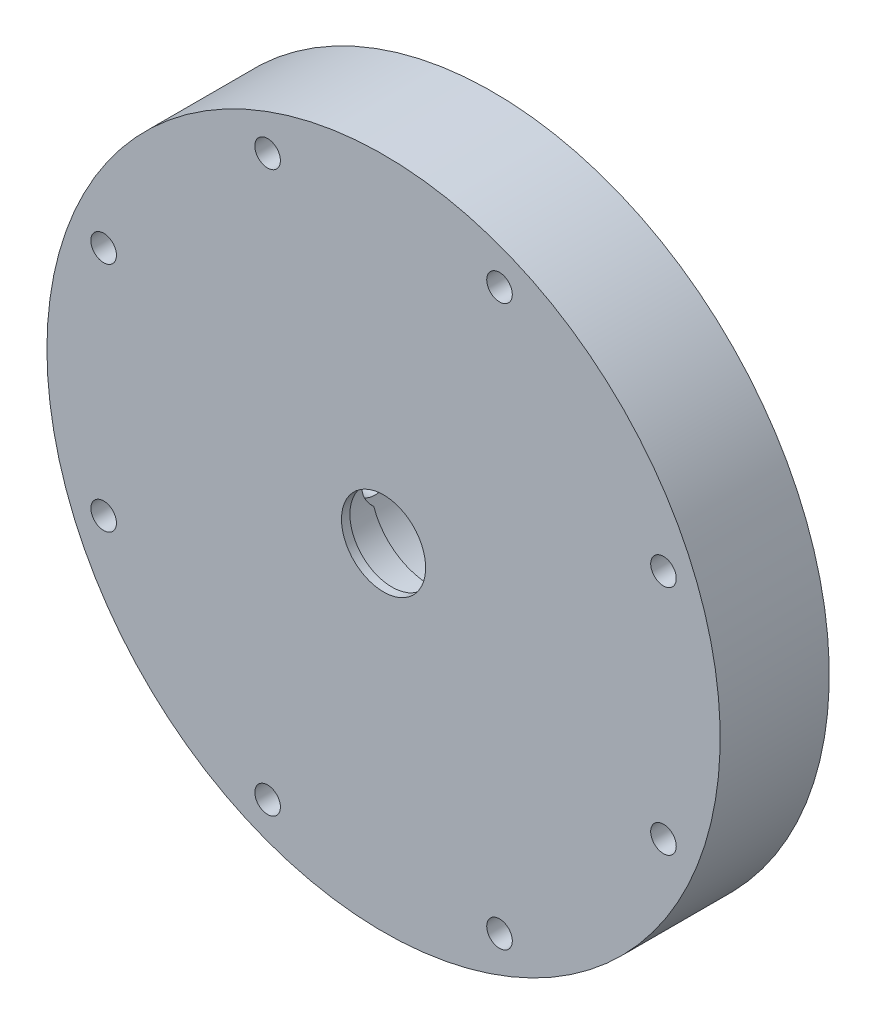
SolidWorks part; units mm, degrees
material "6061-T6 (SS)"
ref_plane "Front Plane" through (0, 0, 0) normal (0, 0, 1) x (1, 0, 0)
ref_plane "Top Plane" through (0, 0, 0) normal (0, 1, 0) x (1, 0, 0)
ref_plane "Right Plane" through (0, 0, 0) normal (1, 0, 0) x (0, 0, -1)
sketch "Sketch16" plane through (0, 0, 0) normal (0, 1, 0) x (1, 0, 0)
  line L0 (7.9375, -25.4) -> (63.5, -25.4)
  line L1 (63.5, -25.4) -> (63.5, 0)
  line L2 (63.5, 0) -> (14.2875, 0)
  line L3 (14.2875, 0) -> (14.2875, -16.6688)
  line L4 (14.2875, -16.6688) -> (11.176, -16.6688)
  line L5 (11.176, -16.6688) -> (11.176, -23.8125)
  line L6 (11.176, -23.8125) -> (7.9375, -23.8125)
  line L7 (7.9375, -23.8125) -> (7.9375, -25.4)
  line L8 (0, 0) -> (0, -25.4) construction
  dimension "D1" = 127
  dimension "D2" = 15.875
  dimension "D3" = 25.4
  dimension "D4" = 1.5875
  dimension "D5" = 7.1437
  dimension "D6" = 22.352
  dimension "D7" = 28.575
revolve "Revolve1" add sketch "Sketch16" angle 360 about L8
sketch "Sketch4" plane through (0, 0, 25.4) normal (0, 0, 1) x (1, 0, 0)
  line L0 (52.7997, -21.8704) -> (58.6664, -24.3004) construction
  line L1 (0, 0) -> (63.5, 0) construction
  circle A0 centre (52.7997, -21.8704) radius 2.413
  circle A2 centre (0, 0) radius 63.5 construction
  dimension "D1" = 4.826
  dimension "D2" = 6.35
  dimension "D3" = 22.5
extrude "Cut-Extrude1" cut sketch "Sketch4" against normal through all
pattern_circular "CirPattern1" count 8 over 360 about axis through (0, 0, 0) along (0, 0, 1) of "Cut-Extrude1"
curve "Curve1"
  spline degree 3 poles (34.3588, 0, 0) (34.3618, -0.072, 0) (34.3677, -0.2162, 0) (34.3749, -0.4324, 0) (34.3809, -0.6488, 0) (34.3855, -0.8653, 0) (34.3887, -1.0818, 0) (34.3906, -1.2984, 0) (34.3911, -1.5151, 0) (34.3903, -1.7318, 0) (34.3881, -1.9486, 0) (34.3846, -2.1655, 0) (34.3797, -2.3823, 0) (34.3735, -2.5992, 0) (34.3659, -2.8162, 0) (34.3569, -3.0331, 0) (34.3466, -3.25, 0) (34.3349, -3.4669, 0) (34.3218, -3.6838, 0) (34.3074, -3.9006, 0) (34.2916, -4.1175, 0) (34.2745, -4.3343, 0) (34.256, -4.551, 0) (34.2361, -4.7677, 0) (34.2149, -4.9843, 0) (34.1923, -5.2008, 0) (34.1683, -5.4172, 0) (34.143, -5.6336, 0) (34.1163, -5.8498, 0) (34.0882, -6.066, 0) (34.0588, -6.282, 0) (34.028, -6.4979, 0) (33.9959, -6.7136, 0) (33.9624, -6.9292, 0) (33.9275, -7.1446, 0) (33.8913, -7.3599, 0) (33.8537, -7.575, 0) (33.8147, -7.79, 0) (33.7744, -8.0047, 0) (33.7327, -8.2192, 0) (33.6897, -8.4336, 0) (33.6453, -8.6477, 0) (33.5996, -8.8616, 0) (33.5525, -9.0752, 0) (33.504, -9.2887, 0) (33.4542, -9.5018, 0) (33.4031, -9.7147, 0) (33.3506, -9.9274, 0) (33.2967, -10.1398, 0) (33.2415, -10.3519, 0) (33.1849, -10.5637, 0) (33.127, -10.7752, 0) (33.0678, -10.9863, 0) (33.0072, -11.1972, 0) (32.9453, -11.4078, 0) (32.882, -11.618, 0) (32.8174, -11.8278, 0) (32.7515, -12.0373, 0) (32.6842, -12.2465, 0) (32.6156, -12.4553, 0) (32.5457, -12.6637, 0) (32.4744, -12.8717, 0) (32.4018, -13.0793, 0) (32.3279, -13.2866, 0) (32.2527, -13.4934, 0) (32.1761, -13.6998, 0) (32.0982, -13.9057, 0) (32.0191, -14.1113, 0) (31.9386, -14.3164, 0) (31.8568, -14.521, 0) (31.7736, -14.7252, 0) (31.6892, -14.9289, 0) (31.6035, -15.1321, 0) (31.5165, -15.3348, 0) (31.4282, -15.5371, 0) (31.3386, -15.7388, 0) (31.2477, -15.9401, 0) (31.1555, -16.1408, 0) (31.062, -16.341, 0) (30.9672, -16.5406, 0) (30.8712, -16.7397, 0) (30.7739, -16.9383, 0) (30.6753, -17.1362, 0) (30.5754, -17.3337, 0) (30.4743, -17.5305, 0) (30.3719, -17.7268, 0) (30.2682, -17.9224, 0) (30.1633, -18.1175, 0) (30.0572, -18.312, 0) (29.9497, -18.5058, 0) (29.8411, -18.699, 0) (29.7312, -18.8916, 0) (29.62, -19.0835, 0) (29.5077, -19.2748, 0) (29.394, -19.4655, 0) (29.2792, -19.6554, 0) (29.1631, -19.8447, 0) (29.0459, -20.0334, 0) (28.9273, -20.2213, 0) (28.8076, -20.4085, 0) (28.6867, -20.595, 0) (28.5646, -20.7809, 0) (28.4413, -20.966, 0) (28.3167, -21.1503, 0) (28.191, -21.334, 0) (28.0641, -21.5168, 0) (27.936, -21.699, 0) (27.8068, -21.8804, 0) (27.6763, -22.061, 0) (27.5447, -22.2408, 0) (27.4119, -22.4199, 0) (27.278, -22.5981, 0) (27.1429, -22.7756, 0) (27.0067, -22.9523, 0) (26.8693, -23.1281, 0) (26.7307, -23.3032, 0) (26.5911, -23.4774, 0) (26.4503, -23.6508, 0) (26.3083, -23.8233, 0) (26.1653, -23.995, 0) (26.0211, -24.1659, 0) (25.8758, -24.3358, 0) (25.7295, -24.5049, 0) (25.582, -24.6732, 0) (25.4334, -24.8405, 0) (25.2837, -25.007, 0) (25.1329, -25.1725, 0) (24.9811, -25.3372, 0) (24.8282, -25.5009, 0) (24.6742, -25.6637, 0) (24.5191, -25.8256, 0) (24.363, -25.9866, 0) (24.2059, -26.1466, 0) (24.0477, -26.3056, 0) (23.8884, -26.4638, 0) (23.7281, -26.6209, 0) (23.5668, -26.7771, 0) (23.4045, -26.9323, 0) (23.2411, -27.0866, 0) (23.0767, -27.2398, 0) (22.9113, -27.392, 0) (22.745, -27.5433, 0) (22.5776, -27.6935, 0) (22.4092, -27.8428, 0) (22.2399, -27.991, 0) (22.0695, -28.1382, 0) (21.8983, -28.2843, 0) (21.726, -28.4294, 0) (21.5528, -28.5735, 0) (21.3786, -28.7165, 0) (21.2035, -28.8584, 0) (21.0274, -28.9993, 0) (20.8505, -29.1391, 0) (20.6726, -29.2779, 0) (20.4937, -29.4155, 0) (20.314, -29.5521, 0) (20.1333, -29.6875, 0) (19.9518, -29.8219, 0) (19.7694, -29.9552, 0) (19.586, -30.0873, 0) (19.4018, -30.2183, 0) (19.2167, -30.3482, 0) (19.0308, -30.477, 0) (18.844, -30.6046, 0) (18.6564, -30.7311, 0) (18.4679, -30.8565, 0) (18.2785, -30.9807, 0) (18.0884, -31.1037, 0) (17.8974, -31.2256, 0) (17.7056, -31.3462, 0) (17.513, -31.4658, 0) (17.3195, -31.5841, 0) (17.1253, -31.7013, 0) (16.9303, -31.8172, 0) (16.7346, -31.932, 0) (16.538, -32.0455, 0) (16.3407, -32.1579, 0) (16.1426, -32.269, 0) (15.9438, -32.379, 0) (15.7442, -32.4877, 0) (15.5439, -32.5951, 0) (15.3429, -32.7014, 0) (15.1411, -32.8064, 0) (14.9387, -32.9101, 0) (14.7355, -33.0127, 0) (14.5316, -33.1139, 0) (14.3271, -33.2139, 0) (14.1218, -33.3127, 0) (13.9159, -33.4102, 0) (13.7093, -33.5064, 0) (13.5021, -33.6013, 0) (13.2942, -33.6949, 0) (13.0857, -33.7873, 0) (12.8765, -33.8784, 0) (12.6667, -33.9682, 0) (12.4563, -34.0567, 0) (12.2453, -34.1439, 0) (12.0336, -34.2297, 0) (11.8214, -34.3143, 0) (11.6086, -34.3976, 0) (11.3952, -34.4795, 0) (11.1812, -34.5601, 0) (10.9667, -34.6394, 0) (10.7516, -34.7174, 0) (10.536, -34.794, 0) (10.3198, -34.8693, 0) (10.1031, -34.9433, 0) (9.8859, -35.0159, 0) (9.6682, -35.0871, 0) (9.4499, -35.1571, 0) (9.2312, -35.2256, 0) (9.012, -35.2928, 0) (8.7923, -35.3586, 0) (8.5721, -35.4231, 0) (8.3515, -35.4862, 0) (8.1304, -35.5479, 0) (7.9088, -35.6083, 0) (7.6869, -35.6672, 0) (7.4645, -35.7248, 0) (7.2416, -35.781, 0) (7.0184, -35.8359, 0) (6.7948, -35.8893, 0) (6.5708, -35.9413, 0) (6.3463, -35.992, 0) (6.1216, -36.0412, 0) (5.8964, -36.089, 0) (5.6709, -36.1355, 0) (5.445, -36.1805, 0) (5.2188, -36.2241, 0) (4.9923, -36.2663, 0) (4.7654, -36.3071, 0) (4.5382, -36.3464, 0) (4.3107, -36.3844, 0) (4.0829, -36.4209, 0) (3.8549, -36.456, 0) (3.6265, -36.4897, 0) (3.3979, -36.5219, 0) (3.169, -36.5527, 0) (2.9398, -36.5821, 0) (2.7105, -36.6101, 0) (2.4808, -36.6366, 0) (2.251, -36.6617, 0) (2.0209, -36.6853, 0) (1.7907, -36.7075, 0) (1.5602, -36.7282, 0) (1.3295, -36.7475, 0) (1.0987, -36.7654, 0) (0.8677, -36.7818, 0) (0.6365, -36.7967, 0) (0.4052, -36.8103, 0) (0.1737, -36.8223, 0) (-0.0579, -36.8329, 0) (-0.2897, -36.842, 0) (-0.5215, -36.8497, 0) (-0.7535, -36.856, 0) (-0.9855, -36.8607, 0) (-1.2177, -36.8641, 0) (-1.4499, -36.8659, 0) (-1.6822, -36.8663, 0) (-1.9146, -36.8652, 0) (-2.147, -36.8627, 0) (-2.3795, -36.8587, 0) (-2.612, -36.8532, 0) (-2.8445, -36.8463, 0) (-3.077, -36.8379, 0) (-3.3096, -36.828, 0) (-3.5421, -36.8167, 0) (-3.7747, -36.8039, 0) (-4.0072, -36.7897, 0) (-4.2397, -36.7739, 0) (-4.4721, -36.7567, 0) (-4.7045, -36.7381, 0) (-4.9368, -36.718, 0) (-5.1691, -36.6964, 0) (-5.4013, -36.6733, 0) (-5.6334, -36.6488, 0) (-5.8654, -36.6228, 0) (-6.0973, -36.5953, 0) (-6.3291, -36.5664, 0) (-6.5608, -36.536, 0) (-6.7924, -36.5041, 0) (-7.0238, -36.4708, 0) (-7.255, -36.436, 0) (-7.4861, -36.3997, 0) (-7.717, -36.362, 0) (-7.9478, -36.3228, 0) (-8.1783, -36.2821, 0) (-8.4087, -36.24, 0) (-8.6389, -36.1964, 0) (-8.8688, -36.1514, 0) (-9.0985, -36.1049, 0) (-9.328, -36.057, 0) (-9.5572, -36.0076, 0) (-9.7862, -35.9567, 0) (-10.015, -35.9044, 0) (-10.2434, -35.8506, 0) (-10.4716, -35.7954, 0) (-10.6995, -35.7387, 0) (-10.9271, -35.6806, 0) (-11.1543, -35.621, 0) (-11.3813, -35.56, 0) (-11.608, -35.4975, 0) (-11.8343, -35.4336, 0) (-12.0602, -35.3683, 0) (-12.2858, -35.3015, 0) (-12.5111, -35.2333, 0) (-12.7359, -35.1636, 0) (-12.9604, -35.0925, 0) (-13.1845, -35.02, 0) (-13.4082, -34.946, 0) (-13.6315, -34.8707, 0) (-13.8544, -34.7939, 0) (-14.0769, -34.7156, 0) (-14.2989, -34.636, 0) (-14.5204, -34.5549, 0) (-14.7416, -34.4724, 0) (-14.9622, -34.3885, 0) (-15.1824, -34.3032, 0) (-15.4021, -34.2165, 0) (-15.6213, -34.1284, 0) (-15.84, -34.0389, 0) (-16.0582, -33.948, 0) (-16.2759, -33.8556, 0) (-16.4931, -33.7619, 0) (-16.7097, -33.6668, 0) (-16.9258, -33.5703, 0) (-17.1414, -33.4725, 0) (-17.3563, -33.3732, 0) (-17.5707, -33.2726, 0) (-17.7846, -33.1705, 0) (-17.9978, -33.0672, 0) (-18.2104, -32.9624, 0) (-18.4225, -32.8563, 0) (-18.6339, -32.7488, 0) (-18.8447, -32.64, 0) (-19.0549, -32.5298, 0) (-19.2644, -32.4182, 0) (-19.4733, -32.3053, 0) (-19.6815, -32.1911, 0) (-19.8891, -32.0755, 0) (-20.0959, -31.9586, 0) (-20.3022, -31.8403, 0) (-20.5077, -31.7208, 0) (-20.7125, -31.5999, 0) (-20.9166, -31.4776, 0) (-21.1199, -31.3541, 0) (-21.3226, -31.2293, 0) (-21.5245, -31.1031, 0) (-21.7257, -30.9756, 0) (-21.9261, -30.8469, 0) (-22.1258, -30.7168, 0) (-22.3247, -30.5855, 0) (-22.5228, -30.4529, 0) (-22.7202, -30.319, 0) (-22.9167, -30.1838, 0) (-23.1125, -30.0473, 0) (-23.3074, -29.9096, 0) (-23.5015, -29.7706, 0) (-23.6948, -29.6303, 0) (-23.8873, -29.4888, 0) (-24.0789, -29.3461, 0) (-24.2697, -29.2021, 0) (-24.4596, -29.0569, 0) (-24.6486, -28.9104, 0) (-24.8368, -28.7627, 0) (-25.0241, -28.6138, 0) (-25.2105, -28.4637, 0) (-25.396, -28.3124, 0) (-25.5806, -28.1598, 0) (-25.7643, -28.0061, 0) (-25.9471, -27.8511, 0) (-26.1289, -27.695, 0) (-26.3098, -27.5377, 0) (-26.4897, -27.3792, 0) (-26.6687, -27.2195, 0) (-26.8468, -27.0587, 0) (-27.0239, -26.8967, 0) (-27.2, -26.7335, 0) (-27.3751, -26.5692, 0) (-27.5492, -26.4038, 0) (-27.7223, -26.2372, 0) (-27.8945, -26.0695, 0) (-28.0656, -25.9006, 0) (-28.2357, -25.7306, 0) (-28.4047, -25.5596, 0) (-28.5728, -25.3874, 0) (-28.7398, -25.2141, 0) (-28.9057, -25.0397, 0) (-29.0706, -24.8642, 0) (-29.2344, -24.6877, 0) (-29.3972, -24.51, 0) (-29.5588, -24.3313, 0) (-29.7194, -24.1515, 0) (-29.8789, -23.9707, 0) (-30.0374, -23.7888, 0) (-30.1947, -23.6059, 0) (-30.3508, -23.422, 0) (-30.5059, -23.237, 0) (-30.6599, -23.051, 0) (-30.8127, -22.864, 0) (-30.9643, -22.6759, 0) (-31.1149, -22.4869, 0) (-31.2642, -22.2968, 0) (-31.4125, -22.1058, 0) (-31.5595, -21.9138, 0) (-31.7054, -21.7208, 0) (-31.8501, -21.5269, 0) (-31.9936, -21.332, 0) (-32.1359, -21.1361, 0) (-32.2771, -20.9393, 0) (-32.417, -20.7416, 0) (-32.5557, -20.5429, 0) (-32.6932, -20.3433, 0) (-32.8295, -20.1428, 0) (-32.9646, -19.9414, 0) (-33.0984, -19.739, 0) (-33.231, -19.5358, 0) (-33.3623, -19.3317, 0) (-33.4924, -19.1267, 0) (-33.6212, -18.9209, 0) (-33.7488, -18.7142, 0) (-33.875, -18.5066, 0) (-34.0001, -18.2982, 0) (-34.1238, -18.0889, 0) (-34.2462, -17.8788, 0) (-34.3674, -17.6679, 0) (-34.4873, -17.4562, 0) (-34.6058, -17.2436, 0) (-34.7231, -17.0303, 0) (-34.839, -16.8161, 0) (-34.9536, -16.6012, 0) (-35.0669, -16.3855, 0) (-35.1789, -16.1691, 0) (-35.2895, -15.9518, 0) (-35.3988, -15.7339, 0) (-35.5067, -15.5152, 0) (-35.6133, -15.2957, 0) (-35.7186, -15.0755, 0) (-35.8224, -14.8546, 0) (-35.925, -14.633, 0) (-36.0261, -14.4107, 0) (-36.1259, -14.1877, 0) (-36.2243, -13.964, 0) (-36.3213, -13.7397, 0) (-36.4169, -13.5146, 0) (-36.5111, -13.289, 0) (-36.604, -13.0626, 0) (-36.6954, -12.8356, 0) (-36.7854, -12.608, 0) (-36.874, -12.3798, 0) (-36.9612, -12.1509, 0) (-37.047, -11.9215, 0) (-37.1314, -11.6914, 0) (-37.2143, -11.4608, 0) (-37.2958, -11.2295, 0) (-37.3758, -10.9977, 0) (-37.4545, -10.7654, 0) (-37.5316, -10.5325, 0) (-37.6074, -10.299, 0) (-37.6817, -10.065, 0) (-37.7545, -9.8305, 0) (-37.8259, -9.5955, 0) (-37.8958, -9.3599, 0) (-37.9642, -9.1239, 0) (-38.0312, -8.8873, 0) (-38.0967, -8.6503, 0) (-38.1607, -8.4128, 0) (-38.2232, -8.1749, 0) (-38.2843, -7.9364, 0) (-38.3439, -7.6976, 0) (-38.402, -7.4583, 0) (-38.4586, -7.2186, 0) (-38.5137, -6.9785, 0) (-38.5673, -6.7379, 0) (-38.6194, -6.497, 0) (-38.67, -6.2557, 0) (-38.7191, -6.014, 0) (-38.7666, -5.7719, 0) (-38.8127, -5.5295, 0) (-38.8573, -5.2867, 0) (-38.9003, -5.0435, 0) (-38.9418, -4.8001, 0) (-38.9818, -4.5563, 0) (-39.0203, -4.3122, 0) (-39.0572, -4.0678, 0) (-39.0926, -3.8231, 0) (-39.1265, -3.5781, 0) (-39.1589, -3.3329, 0) (-39.1897, -3.0874, 0) (-39.2189, -2.8416, 0) (-39.2467, -2.5956, 0) (-39.2729, -2.3493, 0) (-39.2975, -2.1029, 0) (-39.3206, -1.8562, 0) (-39.3422, -1.6093, 0) (-39.3622, -1.3622, 0) (-39.3806, -1.1149, 0) (-39.3975, -0.8674, 0) (-39.4129, -0.6198, 0) (-39.4266, -0.372, 0) (-39.4389, -0.124, 0) (-39.4496, 0.1241, 0) (-39.4587, 0.3723, 0) (-39.4662, 0.6206, 0) (-39.4722, 0.8691, 0) (-39.4766, 1.1176, 0) (-39.4795, 1.3662, 0) (-39.4808, 1.6149, 0) (-39.4806, 1.8637, 0) (-39.4787, 2.1126, 0) (-39.4753, 2.3615, 0) (-39.4704, 2.6104, 0) (-39.4638, 2.8594, 0) (-39.4557, 3.1084, 0) (-39.446, 3.3574, 0) (-39.4348, 3.6064, 0) (-39.422, 3.8554, 0) (-39.4076, 4.1043, 0) (-39.3916, 4.3533, 0) (-39.3741, 4.6022, 0) (-39.355, 4.851, 0) (-39.3343, 5.0998, 0) (-39.3121, 5.3486, 0) (-39.2883, 5.5972, 0) (-39.2629, 5.8458, 0) (-39.2359, 6.0943, 0) (-39.2074, 6.3426, 0) (-39.1773, 6.5909, 0) (-39.1456, 6.839, 0) (-39.1124, 7.087, 0) (-39.0776, 7.3348, 0) (-39.0412, 7.5825, 0) (-39.0033, 7.83, 0) (-38.9637, 8.0773, 0) (-38.9227, 8.3245, 0) (-38.88, 8.5714, 0) (-38.8358, 8.8181, 0) (-38.79, 9.0647, 0) (-38.7427, 9.311, 0) (-38.6938, 9.557, 0) (-38.6433, 9.8028, 0) (-38.5913, 10.0484, 0) (-38.5377, 10.2937, 0) (-38.4825, 10.5387, 0) (-38.4258, 10.7834, 0) (-38.3676, 11.0279, 0) (-38.3077, 11.272, 0) (-38.2464, 11.5158, 0) (-38.1835, 11.7593, 0) (-38.119, 12.0024, 0) (-38.053, 12.2452, 0) (-37.9854, 12.4877, 0) (-37.9163, 12.7297, 0) (-37.8457, 12.9715, 0) (-37.7735, 13.2128, 0) (-37.6998, 13.4537, 0) (-37.6246, 13.6942, 0) (-37.5478, 13.9343, 0) (-37.4694, 14.174, 0) (-37.3896, 14.4133, 0) (-37.3082, 14.6521, 0) (-37.2253, 14.8904, 0) (-37.1409, 15.1283, 0) (-37.055, 15.3658, 0) (-36.9675, 15.6027, 0) (-36.8786, 15.8391, 0) (-36.7881, 16.0751, 0) (-36.6961, 16.3105, 0) (-36.6026, 16.5454, 0) (-36.5076, 16.7798, 0) (-36.4111, 17.0137, 0) (-36.3131, 17.247, 0) (-36.2136, 17.4797, 0) (-36.1127, 17.7119, 0) (-36.0102, 17.9434, 0) (-35.9063, 18.1744, 0) (-35.8008, 18.4048, 0) (-35.6939, 18.6346, 0) (-35.5856, 18.8638, 0) (-35.4757, 19.0924, 0) (-35.3644, 19.3203, 0) (-35.2516, 19.5476, 0) (-35.1374, 19.7742, 0) (-35.0217, 20.0001, 0) (-34.9046, 20.2254, 0) (-34.786, 20.45, 0) (-34.666, 20.6739, 0) (-34.5445, 20.8972, 0) (-34.4216, 21.1197, 0) (-34.2973, 21.3414, 0) (-34.1715, 21.5625, 0) (-34.0443, 21.7828, 0) (-33.9157, 22.0024, 0) (-33.7857, 22.2212, 0) (-33.6542, 22.4393, 0) (-33.5214, 22.6565, 0) (-33.3872, 22.873, 0) (-33.2515, 23.0887, 0) (-33.1145, 23.3036, 0) (-32.9761, 23.5177, 0) (-32.8363, 23.731, 0) (-32.6951, 23.9434, 0) (-32.5526, 24.1551, 0) (-32.4087, 24.3658, 0) (-32.2634, 24.5757, 0) (-32.1168, 24.7848, 0) (-31.9688, 24.993, 0) (-31.8194, 25.2003, 0) (-31.6688, 25.4067, 0) (-31.5168, 25.6122, 0) (-31.3634, 25.8168, 0) (-31.2087, 26.0205, 0) (-31.0528, 26.2232, 0) (-30.8954, 26.425, 0) (-30.7368, 26.6259, 0) (-30.5769, 26.8259, 0) (-30.4157, 27.0249, 0) (-30.2532, 27.2229, 0) (-30.0894, 27.4199, 0) (-29.9243, 27.616, 0) (-29.758, 27.8111, 0) (-29.5903, 28.0051, 0) (-29.4214, 28.1982, 0) (-29.2513, 28.3902, 0) (-29.0799, 28.5812, 0) (-28.9073, 28.7712, 0) (-28.7334, 28.9602, 0) (-28.5583, 29.1481, 0) (-28.3819, 29.3349, 0) (-28.2044, 29.5207, 0) (-28.0256, 29.7054, 0) (-27.8456, 29.889, 0) (-27.6644, 30.0716, 0) (-27.4821, 30.253, 0) (-27.2985, 30.4334, 0) (-27.1138, 30.6126, 0) (-26.9279, 30.7907, 0) (-26.7408, 30.9677, 0) (-26.5525, 31.1435, 0) (-26.3631, 31.3182, 0) (-26.1726, 31.4918, 0) (-25.9809, 31.6642, 0) (-25.7881, 31.8354, 0) (-25.5941, 32.0055, 0) (-25.3991, 32.1744, 0) (-25.2029, 32.3421, 0) (-25.0056, 32.5086, 0) (-24.8073, 32.6739, 0) (-24.6078, 32.8379, 0) (-24.4073, 33.0008, 0) (-24.2056, 33.1625, 0) (-24.003, 33.3229, 0) (-23.7992, 33.4821, 0) (-23.5944, 33.64, 0) (-23.3886, 33.7967, 0) (-23.1817, 33.9521, 0) (-22.9738, 34.1063, 0) (-22.7649, 34.2592, 0) (-22.5549, 34.4108, 0) (-22.344, 34.5612, 0) (-22.132, 34.7102, 0) (-21.9191, 34.8579, 0) (-21.7051, 35.0044, 0) (-21.4902, 35.1495, 0) (-21.2744, 35.2933, 0) (-21.0576, 35.4358, 0) (-20.8398, 35.577, 0) (-20.6211, 35.7168, 0) (-20.4014, 35.8552, 0) (-20.1809, 35.9924, 0) (-19.9594, 36.1281, 0) (-19.737, 36.2626, 0) (-19.5137, 36.3956, 0) (-19.2895, 36.5273, 0) (-19.0644, 36.6576, 0) (-18.8384, 36.7865, 0) (-18.6116, 36.914, 0) (-18.3839, 37.0401, 0) (-18.1554, 37.1648, 0) (-17.926, 37.2881, 0) (-17.6958, 37.41, 0) (-17.4648, 37.5305, 0) (-17.233, 37.6495, 0) (-17.0003, 37.7671, 0) (-16.7669, 37.8833, 0) (-16.5327, 37.998, 0) (-16.2976, 38.1113, 0) (-16.0619, 38.2231, 0) (-15.8253, 38.3335, 0) (-15.588, 38.4424, 0) (-15.35, 38.5499, 0) (-15.1112, 38.6559, 0) (-14.8717, 38.7604, 0) (-14.6315, 38.8634, 0) (-14.3906, 38.9649, 0) (-14.1489, 39.0649, 0) (-13.9066, 39.1635, 0) (-13.6636, 39.2605, 0) (-13.42, 39.356, 0) (-13.1757, 39.4501, 0) (-12.9307, 39.5426, 0) (-12.6851, 39.6335, 0) (-12.4388, 39.723, 0) (-12.1919, 39.8109, 0) (-11.9445, 39.8973, 0) (-11.6964, 39.9822, 0) (-11.4477, 40.0655, 0) (-11.1984, 40.1473, 0) (-10.9486, 40.2275, 0) (-10.6982, 40.3062, 0) (-10.4472, 40.3833, 0) (-10.1957, 40.4588, 0) (-9.9436, 40.5328, 0) (-9.6911, 40.6052, 0) (-9.438, 40.676, 0) (-9.1844, 40.7453, 0) (-8.9303, 40.813, 0) (-8.6757, 40.8791, 0) (-8.4206, 40.9436, 0) (-8.1651, 41.0065, 0) (-7.9091, 41.0679, 0) (-7.6526, 41.1276, 0) (-7.3958, 41.1857, 0) (-7.1385, 41.2422, 0) (-6.8807, 41.2972, 0) (-6.6226, 41.3505, 0) (-6.3641, 41.4022, 0) (-6.1051, 41.4523, 0) (-5.8458, 41.5007, 0) (-5.5862, 41.5476, 0) (-5.3262, 41.5928, 0) (-5.0658, 41.6364, 0) (-4.8051, 41.6784, 0) (-4.544, 41.7187, 0) (-4.2827, 41.7574, 0) (-4.021, 41.7944, 0) (-3.7591, 41.8299, 0) (-3.4968, 41.8637, 0) (-3.2343, 41.8958, 0) (-2.9715, 41.9263, 0) (-2.7085, 41.9551, 0) (-2.4452, 41.9823, 0) (-2.1817, 42.0079, 0) (-1.9179, 42.0318, 0) (-1.654, 42.054, 0) (-1.3898, 42.0746, 0) (-1.1254, 42.0935, 0) (-0.8609, 42.1108, 0) (-0.5962, 42.1264, 0) (-0.3313, 42.1403, 0) (-0.0663, 42.1526, 0) (0.1989, 42.1632, 0) (0.4642, 42.1721, 0) (0.7296, 42.1794, 0) (0.9952, 42.185, 0) (1.2608, 42.1889, 0) (1.5265, 42.1912, 0) (1.7923, 42.1918, 0) (2.0582, 42.1907, 0) (2.3241, 42.1879, 0) (2.5901, 42.1835, 0) (2.8561, 42.1774, 0) (3.1221, 42.1696, 0) (3.3881, 42.1601, 0) (3.6542, 42.149, 0) (3.9202, 42.1362, 0) (4.1863, 42.1217, 0) (4.4523, 42.1055, 0) (4.7182, 42.0876, 0) (4.9841, 42.0681, 0) (5.25, 42.0469, 0) (5.5158, 42.024, 0) (5.7815, 41.9994, 0) (6.0471, 41.9732, 0) (6.3126, 41.9452, 0) (6.578, 41.9156, 0) (6.8433, 41.8843, 0) (7.1084, 41.8514, 0) (7.3734, 41.8167, 0) (7.6383, 41.7804, 0) (7.903, 41.7424, 0) (8.1675, 41.7027, 0) (8.4318, 41.6614, 0) (8.6959, 41.6184, 0) (8.9598, 41.5737, 0) (9.2235, 41.5273, 0) (9.487, 41.4792, 0) (9.7502, 41.4295, 0) (10.0132, 41.3782, 0) (10.2759, 41.3251, 0) (10.5384, 41.2704, 0) (10.8005, 41.214, 0) (11.0624, 41.156, 0) (11.324, 41.0962, 0) (11.5852, 41.0349, 0) (11.8462, 40.9718, 0) (12.1068, 40.9071, 0) (12.367, 40.8408, 0) (12.6269, 40.7728, 0) (12.8865, 40.7031, 0) (13.1456, 40.6318, 0) (13.4044, 40.5589, 0) (13.6628, 40.4843, 0) (13.9207, 40.408, 0) (14.1783, 40.3302, 0) (14.4354, 40.2506, 0) (14.6921, 40.1695, 0) (14.9483, 40.0867, 0) (15.2041, 40.0022, 0) (15.4594, 39.9161, 0) (15.7142, 39.8285, 0) (15.9685, 39.7391, 0) (16.2223, 39.6482, 0) (16.4756, 39.5556, 0) (16.7284, 39.4614, 0) (16.9807, 39.3656, 0) (17.2324, 39.2682, 0) (17.4836, 39.1692, 0) (17.7342, 39.0686, 0) (17.9842, 38.9664, 0) (18.2336, 38.8626, 0) (18.4825, 38.7571, 0) (18.7307, 38.6501, 0) (18.9783, 38.5415, 0) (19.2254, 38.4313, 0) (19.4717, 38.3196, 0) (19.7174, 38.2062, 0) (19.9625, 38.0913, 0) (20.2069, 37.9748, 0) (20.4506, 37.8568, 0) (20.6937, 37.7372, 0) (20.936, 37.616, 0) (21.1777, 37.4933, 0) (21.4186, 37.369, 0) (21.6588, 37.2431, 0) (21.8983, 37.1158, 0) (22.137, 36.9869, 0) (22.3749, 36.8564, 0) (22.6121, 36.7244, 0) (22.8486, 36.5909, 0) (23.0842, 36.4559, 0) (23.3191, 36.3194, 0) (23.5531, 36.1813, 0) (23.7863, 36.0418, 0) (24.0187, 35.9007, 0) (24.2503, 35.7582, 0) (24.4811, 35.6141, 0) (24.7109, 35.4686, 0) (24.9399, 35.3216, 0) (25.1681, 35.1731, 0) (25.3954, 35.0231, 0) (25.6217, 34.8717, 0) (25.8472, 34.7188, 0) (26.0718, 34.5645, 0) (26.2954, 34.4087, 0) (26.5181, 34.2514, 0) (26.7399, 34.0927, 0) (26.9608, 33.9326, 0) (27.1806, 33.7711, 0) (27.3996, 33.6081, 0) (27.6175, 33.4437, 0) (27.8345, 33.2779, 0) (28.0504, 33.1107, 0) (28.2654, 32.9421, 0) (28.4793, 32.7721, 0) (28.6923, 32.6007, 0) (28.9042, 32.428, 0) (29.115, 32.2538, 0) (29.3249, 32.0783, 0) (29.5336, 31.9014, 0) (29.7413, 31.7232, 0) (29.9479, 31.5436, 0) (30.1535, 31.3627, 0) (30.3579, 31.1804, 0) (30.5613, 30.9969, 0) (30.7635, 30.8119, 0) (30.9647, 30.6257, 0) (31.1647, 30.4382, 0) (31.3635, 30.2493, 0) (31.5613, 30.0592, 0) (31.7579, 29.8677, 0) (31.9533, 29.675, 0) (32.1475, 29.481, 0) (32.3406, 29.2858, 0) (32.5325, 29.0892, 0) (32.7232, 28.8915, 0) (32.9127, 28.6924, 0) (33.101, 28.4922, 0) (33.2881, 28.2907, 0) (33.4739, 28.0879, 0) (33.6585, 27.884, 0) (33.8419, 27.6788, 0) (34.024, 27.4725, 0) (34.2049, 27.2649, 0) (34.3845, 27.0562, 0) (34.5628, 26.8463, 0) (34.7399, 26.6352, 0) (34.9157, 26.4229, 0) (35.0901, 26.2095, 0) (35.2633, 25.9949, 0) (35.4352, 25.7792, 0) (35.6057, 25.5624, 0) (35.7749, 25.3444, 0) (35.9428, 25.1253, 0) (36.1094, 24.9051, 0) (36.2746, 24.6838, 0) (36.4384, 24.4615, 0) (36.6009, 24.238, 0) (36.762, 24.0135, 0) (36.9217, 23.7878, 0) (37.0801, 23.5612, 0) (37.237, 23.3335, 0) (37.3926, 23.1047, 0) (37.5468, 22.8749, 0) (37.6995, 22.6441, 0) (37.8509, 22.4122, 0) (38.0008, 22.1794, 0) (38.1492, 21.9456, 0) (38.2963, 21.7107, 0) (38.4419, 21.4749, 0) (38.586, 21.2381, 0) (38.7287, 21.0004, 0) (38.8699, 20.7617, 0) (39.0097, 20.522, 0) (39.148, 20.2814, 0) (39.2848, 20.0399, 0) (39.4201, 19.7975, 0) (39.5539, 19.5541, 0) (39.6862, 19.3099, 0) (39.817, 19.0648, 0) (39.9463, 18.8188, 0) (40.0741, 18.5719, 0) (40.2003, 18.3241, 0) (40.325, 18.0755, 0) (40.4482, 17.8261, 0) (40.5698, 17.5758, 0) (40.6899, 17.3247, 0) (40.8085, 17.0728, 0) (40.9254, 16.8201, 0) (41.0409, 16.5666, 0) (41.1547, 16.3123, 0) (41.267, 16.0572, 0) (41.3777, 15.8013, 0) (41.4868, 15.5447, 0) (41.5943, 15.2874, 0) (41.7002, 15.0293, 0) (41.8045, 14.7705, 0) (41.9073, 14.5109, 0) (42.0084, 14.2507, 0) (42.1078, 13.9898, 0) (42.2057, 13.7281, 0) (42.302, 13.4658, 0) (42.3966, 13.2029, 0) (42.4896, 12.9392, 0) (42.5809, 12.675, 0) (42.6706, 12.41, 0) (42.7587, 12.1445, 0) (42.8451, 11.8783, 0) (42.9298, 11.6116, 0) (43.0129, 11.3442, 0) (43.0943, 11.0763, 0) (43.1741, 10.8078, 0) (43.2522, 10.5387, 0) (43.3286, 10.269, 0) (43.4033, 9.9989, 0) (43.4763, 9.7281, 0) (43.5477, 9.4569, 0) (43.6173, 9.1852, 0) (43.6853, 8.9129, 0) (43.7516, 8.6402, 0) (43.8161, 8.3669, 0) (43.879, 8.0932, 0) (43.9402, 7.8191, 0) (43.9996, 7.5445, 0) (44.0573, 7.2694, 0) (44.1133, 6.994, 0) (44.1676, 6.7181, 0) (44.2202, 6.4418, 0) (44.271, 6.1651, 0) (44.3201, 5.888, 0) (44.3675, 5.6106, 0) (44.4131, 5.3328, 0) (44.457, 5.0546, 0) (44.4992, 4.7761, 0) (44.5396, 4.4973, 0) (44.5782, 4.2181, 0) (44.6151, 3.9387, 0) (44.6503, 3.6589, 0) (44.6837, 3.3789, 0) (44.7154, 3.0985, 0) (44.7453, 2.8179, 0) (44.7734, 2.5371, 0) (44.7998, 2.256, 0) (44.8244, 1.9747, 0) (44.8472, 1.6932, 0) (44.8683, 1.4114, 0) (44.8876, 1.1295, 0) (44.9051, 0.8474, 0) (44.9209, 0.5651, 0) (44.935, 0.2826, 0) (44.9429, 0.0942, 0) (44.9468, 0, 0) knots 0 0 0 0 0.000871 0.001741 0.002613 0.003484 0.004355 0.005227 0.006099 0.006972 0.007844 0.008717 0.00959 0.010463 0.011337 0.01221 0.013084 0.013958 0.014833 0.015708 0.016583 0.017458 0.018333 0.019209 0.020085 0.020961 0.021837 0.022714 0.023591 0.024468 0.025345 0.026223 0.027101 0.027979 0.028857 0.029736 0.030614 0.031493 0.032373 0.033252 0.034132 0.035012 0.035892 0.036773 0.037654 0.038535 0.039416 0.040297 0.041179 0.042061 0.042943 0.043826 0.044709 0.045592 0.046475 0.047358 0.048242 0.049126 0.05001 0.050895 0.051779 0.052664 0.053549 0.054435 0.05532 0.056206 0.057093 0.057979 0.058866 0.059753 0.06064 0.061527 0.062415 0.063303 0.064191 0.065079 0.065968 0.066857 0.067746 0.068635 0.069525 0.070415 0.071305 0.072195 0.073086 0.073977 0.074868 0.075759 0.076651 0.077543 0.078435 0.079327 0.08022 0.081113 0.082006 0.082899 0.083793 0.084687 0.085581 0.086475 0.08737 0.088265 0.08916 0.090055 0.090951 0.091847 0.092743 0.093639 0.094536 0.095433 0.09633 0.097227 0.098125 0.099023 0.099921 0.100819 0.101718 0.102617 0.103516 0.104415 0.105315 0.106215 0.107115 0.108015 0.108916 0.109817 0.110718 0.111619 0.112521 0.113423 0.114325 0.115227 0.11613 0.117033 0.117936 0.118839 0.119743 0.120647 0.121551 0.122455 0.12336 0.124265 0.12517 0.126076 0.126981 0.127887 0.128793 0.1297 0.130607 0.131513 0.132421 0.133328 0.134236 0.135144 0.136052 0.13696 0.137869 0.138778 0.139687 0.140597 0.141507 0.142417 0.143327 0.144237 0.145148 0.146059 0.14697 0.147882 0.148794 0.149706 0.150618 0.15153 0.152443 0.153356 0.154269 0.155183 0.156097 0.157011 0.157925 0.15884 0.159755 0.16067 0.161585 0.162501 0.163416 0.164332 0.165249 0.166165 0.167082 0.167999 0.168917 0.169834 0.170752 0.17167 0.172589 0.173508 0.174426 0.175346 0.176265 0.177185 0.178105 0.179025 0.179945 0.180866 0.181787 0.182708 0.18363 0.184551 0.185473 0.186396 0.187318 0.188241 0.189164 0.190087 0.191011 0.191935 0.192859 0.193783 0.194707 0.195632 0.196557 0.197483 0.198408 0.199334 0.20026 0.201187 0.202113 0.20304 0.203967 0.204895 0.205822 0.20675 0.207678 0.208607 0.209535 0.210464 0.211394 0.212323 0.213253 0.214183 0.215113 0.216044 0.216974 0.217905 0.218837 0.219768 0.2207 0.221632 0.222564 0.223497 0.22443 0.225363 0.226296 0.22723 0.228164 0.229098 0.230032 0.230967 0.231902 0.232837 0.233772 0.234708 0.235644 0.23658 0.237516 0.238453 0.23939 0.240327 0.241265 0.242203 0.243141 0.244079 0.245017 0.245956 0.246895 0.247835 0.248774 0.249714 0.250654 0.251595 0.252535 0.253476 0.254417 0.255359 0.2563 0.257242 0.258184 0.259127 0.26007 0.261013 0.261956 0.262899 0.263843 0.264787 0.265731 0.266676 0.267621 0.268566 0.269511 0.270457 0.271402 0.272349 0.273295 0.274242 0.275188 0.276136 0.277083 0.278031 0.278979 0.279927 0.280875 0.281824 0.282773 0.283722 0.284672 0.285622 0.286572 0.287522 0.288472 0.289423 0.290374 0.291326 0.292277 0.293229 0.294181 0.295134 0.296086 0.297039 0.297993 0.298946 0.2999 0.300854 0.301808 0.302762 0.303717 0.304672 0.305628 0.306583 0.307539 0.308495 0.309451 0.310408 0.311365 0.312322 0.313279 0.314237 0.315195 0.316153 0.317112 0.31807 0.319029 0.319989 0.320948 0.321908 0.322868 0.323828 0.324789 0.32575 0.326711 0.327672 0.328634 0.329596 0.330558 0.33152 0.332483 0.333446 0.334409 0.335373 0.336336 0.3373 0.338265 0.339229 0.340194 0.341159 0.342124 0.34309 0.344056 0.345022 0.345988 0.346955 0.347922 0.348889 0.349857 0.350824 0.351792 0.352761 0.353729 0.354698 0.355667 0.356636 0.357606 0.358576 0.359546 0.360516 0.361487 0.362458 0.363429 0.3644 0.365372 0.366344 0.367316 0.368289 0.369261 0.370235 0.371208 0.372181 0.373155 0.374129 0.375104 0.376078 0.377053 0.378028 0.379004 0.37998 0.380956 0.381932 0.382908 0.383885 0.384862 0.385839 0.386817 0.387795 0.388773 0.389751 0.39073 0.391709 0.392688 0.393667 0.394647 0.395627 0.396607 0.397588 0.398569 0.39955 0.400531 0.401513 0.402494 0.403477 0.404459 0.405442 0.406425 0.407408 0.408391 0.409375 0.410359 0.411343 0.412328 0.413312 0.414298 0.415283 0.416268 0.417254 0.41824 0.419227 0.420214 0.4212 0.422188 0.423175 0.424163 0.425151 0.426139 0.427128 0.428117 0.429106 0.430095 0.431085 0.432075 0.433065 0.434055 0.435046 0.436037 0.437028 0.43802 0.439011 0.440003 0.440996 0.441988 0.442981 0.443974 0.444968 0.445961 0.446955 0.447949 0.448944 0.449939 0.450934 0.451929 0.452925 0.45392 0.454916 0.455913 0.456909 0.457906 0.458904 0.459901 0.460899 0.461897 0.462895 0.463893 0.464892 0.465891 0.466891 0.46789 0.46889 0.46989 0.470891 0.471891 0.472892 0.473893 0.474895 0.475897 0.476899 0.477901 0.478904 0.479906 0.48091 0.481913 0.482917 0.483921 0.484925 0.485929 0.486934 0.487939 0.488944 0.48995 0.490956 0.491962 0.492968 0.493975 0.494982 0.495989 0.496996 0.498004 0.499012 0.50002 0.501029 0.502038 0.503047 0.504056 0.505066 0.506076 0.507086 0.508096 0.509107 0.510118 0.511129 0.512141 0.513153 0.514165 0.515177 0.51619 0.517202 0.518216 0.519229 0.520243 0.521257 0.522271 0.523285 0.5243 0.525315 0.526331 0.527346 0.528362 0.529378 0.530395 0.531411 0.532428 0.533446 0.534463 0.535481 0.536499 0.537517 0.538536 0.539555 0.540574 0.541594 0.542613 0.543633 0.544653 0.545674 0.546695 0.547716 0.548737 0.549759 0.550781 0.551803 0.552825 0.553848 0.554871 0.555894 0.556918 0.557942 0.558966 0.55999 0.561015 0.562039 0.563065 0.56409 0.565116 0.566142 0.567168 0.568195 0.569221 0.570249 0.571276 0.572304 0.573331 0.57436 0.575388 0.576417 0.577446 0.578475 0.579505 0.580534 0.581565 0.582595 0.583626 0.584657 0.585688 0.586719 0.587751 0.588783 0.589815 0.590848 0.591881 0.592914 0.593947 0.594981 0.596015 0.597049 0.598084 0.599118 0.600153 0.601189 0.602224 0.60326 0.604296 0.605333 0.60637 0.607406 0.608444 0.609481 0.610519 0.611557 0.612595 0.613634 0.614673 0.615712 0.616752 0.617791 0.618831 0.619872 0.620912 0.621953 0.622994 0.624036 0.625077 0.626119 0.627161 0.628204 0.629247 0.63029 0.631333 0.632377 0.63342 0.634465 0.635509 0.636554 0.637599 0.638644 0.639689 0.640735 0.641781 0.642828 0.643874 0.644921 0.645968 0.647016 0.648064 0.649112 0.65016 0.651208 0.652257 0.653306 0.654356 0.655405 0.656455 0.657506 0.658556 0.659607 0.660658 0.661709 0.662761 0.663813 0.664865 0.665917 0.66697 0.668023 0.669076 0.67013 0.671184 0.672238 0.673292 0.674347 0.675402 0.676457 0.677513 0.678568 0.679624 0.680681 0.681737 0.682794 0.683851 0.684909 0.685967 0.687025 0.688083 0.689141 0.6902 0.691259 0.692319 0.693378 0.694438 0.695499 0.696559 0.69762 0.698681 0.699742 0.700804 0.701866 0.702928 0.70399 0.705053 0.706116 0.707179 0.708243 0.709307 0.710371 0.711435 0.7125 0.713565 0.71463 0.715696 0.716761 0.717827 0.718894 0.71996 0.721027 0.722094 0.723162 0.72423 0.725298 0.726366 0.727435 0.728503 0.729573 0.730642 0.731712 0.732782 0.733852 0.734922 0.735993 0.737064 0.738136 0.739207 0.740279 0.741351 0.742424 0.743497 0.74457 0.745643 0.746717 0.747791 0.748865 0.749939 0.751014 0.752089 0.753164 0.75424 0.755316 0.756392 0.757468 0.758545 0.759622 0.760699 0.761777 0.762854 0.763932 0.765011 0.766089 0.767168 0.768248 0.769327 0.770407 0.771487 0.772567 0.773648 0.774729 0.77581 0.776891 0.777973 0.779055 0.780137 0.78122 0.782303 0.783386 0.784469 0.785553 0.786637 0.787721 0.788806 0.789891 0.790976 0.792061 0.793147 0.794233 0.795319 0.796405 0.797492 0.798579 0.799667 0.800754 0.801842 0.80293 0.804019 0.805108 0.806197 0.807286 0.808375 0.809465 0.810555 0.811646 0.812737 0.813828 0.814919 0.816011 0.817102 0.818195 0.819287 0.82038 0.821473 0.822566 0.823659 0.824753 0.825847 0.826942 0.828036 0.829131 0.830227 0.831322 0.832418 0.833514 0.83461 0.835707 0.836804 0.837901 0.838999 0.840096 0.841194 0.842293 0.843391 0.84449 0.845589 0.846689 0.847789 0.848889 0.849989 0.85109 0.85219 0.853292 0.854393 0.855495 0.856597 0.857699 0.858802 0.859905 0.861008 0.862111 0.863215 0.864319 0.865423 0.866528 0.867633 0.868738 0.869843 0.870949 0.872055 0.873161 0.874268 0.875374 0.876481 0.877589 0.878697 0.879804 0.880913 0.882021 0.88313 0.884239 0.885349 0.886458 0.887568 0.888678 0.889789 0.8909 0.892011 0.893122 0.894234 0.895346 0.896458 0.89757 0.898683 0.899796 0.90091 0.902023 0.903137 0.904251 0.905366 0.906481 0.907596 0.908711 0.909827 0.910943 0.912059 0.913175 0.914292 0.915409 0.916526 0.917644 0.918762 0.91988 0.920998 0.922117 0.923236 0.924356 0.925475 0.926595 0.927715 0.928836 0.929956 0.931077 0.932199 0.93332 0.934442 0.935564 0.936687 0.93781 0.938933 0.940056 0.94118 0.942303 0.943428 0.944552 0.945677 0.946802 0.947927 0.949053 0.950179 0.951305 0.952431 0.953558 0.954685 0.955812 0.95694 0.958068 0.959196 0.960324 0.961453 0.962582 0.963711 0.964841 0.965971 0.967101 0.968231 0.969362 0.970493 0.971624 0.972756 0.973888 0.97502 0.976153 0.977285 0.978418 0.979552 0.980685 0.981819 0.982953 0.984088 0.985222 0.986357 0.987493 0.988628 0.989764 0.9909 0.992037 0.993174 0.994311 0.995448 0.996585 0.997723 0.998862 1 1 1 1
sketch "Sketch18" plane through (0, 0, 0) normal (0, 0, -1) x (-1, 0, 0)
  line L0 (-41.7746, -3.3079) -> (-38.4379, -3.3079)
  arc A0 (-44.9468, 0) -> (-41.7746, -3.3079) centre (-41.7746, -0.1329) ccw
  arc A1 (-38.4379, -3.3079) -> (-35.2656, -0.0003) centre (-38.4379, -0.1329) ccw
  arc A2 (-35.2656, -0.0003) -> (-34.3588, 0) centre (-34.8122, 0.0186) cw
  arc A3 (-38.4379, -3.3079) -> (-33.9289, -7.1346) centre (-38.4379, -7.8776) cw
  spline S0 degree 3 poles (-9021.8063, 410.464) (-4.19, 44.6435) (-33.6054, 22.6861) (-34.3749, -0.4324) (-34.3809, -0.6488) (-34.39, -1.0819) (-34.3957, -2.0941) (-34.3424, -3.6139) (-34.1824, -5.4201) (-33.9415, -7.1482) (-33.6134, -8.8659) (-33.1986, -10.5687) (-32.6976, -12.2522) (-32.1114, -13.9121) (-31.441, -15.5441) (-30.6877, -17.144) (-29.8532, -18.7074) (-28.939, -20.2303) (-27.9473, -21.7085) (-26.88, -23.1383) (-25.7397, -24.5156) (-24.5289, -25.8368) (-23.2503, -27.0983) (-21.9069, -28.2965) (-20.5017, -29.4282) (-19.0382, -30.4901) (-17.5197, -31.4792) (-15.9499, -32.3928) (-14.3324, -33.228) (-12.6714, -33.9826) (-10.9706, -34.6541) (-9.2344, -35.2405) (-7.4669, -35.7399) (-5.6726, -36.1506) (-3.8558, -36.4713) (-2.0211, -36.7006) (-0.1731, -36.8377) (1.6836, -36.8816) (3.5443, -36.832) (5.4042, -36.6885) (7.2587, -36.451) (9.103, -36.1198) (10.9323, -35.6953) (12.7419, -35.1781) (14.5271, -34.5691) (16.2833, -33.8695) (18.0059, -33.0806) (19.6903, -32.2042) (21.3321, -31.2419) (22.9268, -30.1959) (24.4703, -29.0686) (25.9584, -27.8623) (27.387, -26.5798) (28.7522, -25.2241) (30.0503, -23.7982) (31.2777, -22.3056) (32.4309, -20.7497) (33.5067, -19.1341) (34.502, -17.4628) (35.4138, -15.7398) (36.2396, -13.9692) (36.9769, -12.1553) (37.6233, -10.3026) (38.1768, -8.4156) (38.6356, -6.499) (38.9982, -4.5575) (39.2631, -2.596) (39.4293, -0.6193) (39.496, 1.3675) (39.4624, 3.3595) (39.3284, 5.3515) (39.0938, 7.3386) (38.7587, 9.3155) (38.3235, 11.2774) (37.7891, 13.219) (37.1561, 15.1353) (36.426, 17.0214) (35.6001, 18.8723) (34.6801, 20.6832) (33.6679, 22.4492) (32.5657, 24.1657) (31.376, 25.8281) (30.1015, 27.4319) (28.7449, 28.9728) (27.3094, 30.4465) (25.7983, 31.8492) (24.2152, 33.1767) (22.5637, 34.4256) (20.8479, 35.5922) (19.0717, 36.6732) (17.2395, 37.6655) (15.3557, 38.5662) (13.4249, 39.3727) (11.4518, 40.0824) (9.4412, 40.6932) (7.3981, 41.203) (5.3277, 41.6102) (3.2349, 41.9133) (1.1252, 42.1111) (-0.9963, 42.2026) (-3.1241, 42.1871) (-5.2529, 42.0643) (-7.3772, 41.834) (-9.4917, 41.4964) (-11.5908, 41.0518) (-13.6692, 40.5009) (-15.7214, 39.8448) (-17.7422, 39.0846) (-19.7263, 38.2218) (-21.6685, 37.2583) (-23.5635, 36.196) (-25.4065, 35.0373) (-27.1926, 33.7847) (-28.9168, 32.441) (-30.5746, 31.0093) (-32.1614, 29.4928) (-33.673, 27.8951) (-35.1052, 26.2198) (-36.454, 24.4711) (-37.7156, 22.6529) (-38.8865, 20.7697) (-39.9633, 18.8259) (-40.9428, 16.8264) (-41.8222, 14.7759) (-42.5989, 12.6795) (-43.2704, 10.5424) (-43.8346, 8.3697) (-44.2896, 6.1669) (-44.6194, 4.0326) (-44.7887, 2.4435) (-44.8619, 1.5054) (-44.8876, 1.1295) (-44.9051, 0.8474) (-44.9209, 0.5651) (-46.2883, -26.8465) (-16.0156, -55.5887) (-9036.082, 323.3703) knots -0.276661 -0.276661 -0.276661 -0.276661 0.000871 0.001741 0.002613 0.003484 0.006972 0.014833 0.021837 0.028857 0.035892 0.042943 0.05001 0.057093 0.064191 0.071305 0.078435 0.085581 0.092743 0.099921 0.107115 0.114325 0.121551 0.128793 0.136052 0.143327 0.150618 0.157925 0.165249 0.172589 0.179945 0.187318 0.194707 0.202113 0.209535 0.216974 0.22443 0.231902 0.23939 0.246895 0.254417 0.261956 0.269511 0.277083 0.284672 0.292277 0.2999 0.307539 0.315195 0.322868 0.330558 0.338265 0.345988 0.353729 0.361487 0.369261 0.377053 0.384862 0.392688 0.400531 0.408391 0.416268 0.424163 0.432075 0.440003 0.447949 0.455913 0.463893 0.471891 0.479906 0.487939 0.495989 0.504056 0.512141 0.520243 0.528362 0.536499 0.544653 0.552825 0.561015 0.569221 0.577446 0.585688 0.593947 0.602224 0.610519 0.618831 0.627161 0.635509 0.643874 0.652257 0.660658 0.669076 0.677513 0.685967 0.694438 0.702928 0.711435 0.71996 0.728503 0.737064 0.745643 0.75424 0.762854 0.771487 0.780137 0.788806 0.797492 0.806197 0.814919 0.823659 0.832418 0.841194 0.849989 0.858802 0.867633 0.876481 0.885349 0.894234 0.903137 0.912059 0.920998 0.929956 0.938933 0.947927 0.95694 0.965971 0.97502 0.984088 0.992037 0.994311 0.995448 0.996585 0.997723 0.998862 1.327946 1.327946 1.327946 1.327946 only from (-34.3588, 0) to (-44.9468, 0) construction
  spline S1 degree 3 poles (-34.3588, 0) (-34.3618, -0.072) (-34.3677, -0.2162) (-34.3749, -0.4324) (-34.3809, -0.6488) (-34.39, -1.0819) (-34.3957, -2.0941) (-34.3424, -3.6139) (-34.1824, -5.4201) (-33.9415, -7.1482) (-33.6134, -8.8659) (-33.1986, -10.5687) (-32.6976, -12.2522) (-32.1114, -13.9121) (-31.441, -15.5441) (-30.6877, -17.144) (-29.8532, -18.7074) (-28.939, -20.2303) (-27.9473, -21.7085) (-26.88, -23.1383) (-25.7397, -24.5156) (-24.5289, -25.8368) (-23.2503, -27.0983) (-21.9069, -28.2965) (-20.5017, -29.4282) (-19.0382, -30.4901) (-17.5197, -31.4792) (-15.9499, -32.3928) (-14.3324, -33.228) (-12.6714, -33.9826) (-10.9706, -34.6541) (-9.2344, -35.2405) (-7.4669, -35.7399) (-5.6726, -36.1506) (-3.8558, -36.4713) (-2.0211, -36.7006) (-0.1731, -36.8377) (1.6836, -36.8816) (3.5443, -36.832) (5.4042, -36.6885) (7.2587, -36.451) (9.103, -36.1198) (10.9323, -35.6953) (12.7419, -35.1781) (14.5271, -34.5691) (16.2833, -33.8695) (18.0059, -33.0806) (19.6903, -32.2042) (21.3321, -31.2419) (22.9268, -30.1959) (24.4703, -29.0686) (25.9584, -27.8623) (27.387, -26.5798) (28.7522, -25.2241) (30.0503, -23.7982) (31.2777, -22.3056) (32.4309, -20.7497) (33.5067, -19.1341) (34.502, -17.4628) (35.4138, -15.7398) (36.2396, -13.9692) (36.9769, -12.1553) (37.6233, -10.3026) (38.1768, -8.4156) (38.6356, -6.499) (38.9982, -4.5575) (39.2631, -2.596) (39.4293, -0.6193) (39.496, 1.3675) (39.4624, 3.3595) (39.3284, 5.3515) (39.0938, 7.3386) (38.7587, 9.3155) (38.3235, 11.2774) (37.7891, 13.219) (37.1561, 15.1353) (36.426, 17.0214) (35.6001, 18.8723) (34.6801, 20.6832) (33.6679, 22.4492) (32.5657, 24.1657) (31.376, 25.8281) (30.1015, 27.4319) (28.7449, 28.9728) (27.3094, 30.4465) (25.7983, 31.8492) (24.2152, 33.1767) (22.5637, 34.4256) (20.8479, 35.5922) (19.0717, 36.6732) (17.2395, 37.6655) (15.3557, 38.5662) (13.4249, 39.3727) (11.4518, 40.0824) (9.4412, 40.6932) (7.3981, 41.203) (5.3277, 41.6102) (3.2349, 41.9133) (1.1252, 42.1111) (-0.9963, 42.2026) (-3.1241, 42.1871) (-5.2529, 42.0643) (-7.3772, 41.834) (-9.4917, 41.4964) (-11.5908, 41.0518) (-13.6692, 40.5009) (-15.7214, 39.8448) (-17.7422, 39.0846) (-19.7263, 38.2218) (-21.6685, 37.2583) (-23.5635, 36.196) (-25.4065, 35.0373) (-27.1926, 33.7847) (-28.9168, 32.441) (-30.5746, 31.0093) (-32.1614, 29.4928) (-33.673, 27.8951) (-35.1052, 26.2198) (-36.454, 24.4711) (-37.7156, 22.6529) (-38.8865, 20.7697) (-39.9633, 18.8259) (-40.9428, 16.8264) (-41.8222, 14.7759) (-42.5989, 12.6795) (-43.2704, 10.5424) (-43.8346, 8.3697) (-44.2896, 6.1669) (-44.6194, 4.0326) (-44.7887, 2.4435) (-44.8619, 1.5054) (-44.8876, 1.1295) (-44.9051, 0.8474) (-44.9209, 0.5651) (-44.935, 0.2826) (-44.9429, 0.0942) (-44.9468, 0) knots 0 0 0 0 0.000871 0.001741 0.002613 0.003484 0.006972 0.014833 0.021837 0.028857 0.035892 0.042943 0.05001 0.057093 0.064191 0.071305 0.078435 0.085581 0.092743 0.099921 0.107115 0.114325 0.121551 0.128793 0.136052 0.143327 0.150618 0.157925 0.165249 0.172589 0.179945 0.187318 0.194707 0.202113 0.209535 0.216974 0.22443 0.231902 0.23939 0.246895 0.254417 0.261956 0.269511 0.277083 0.284672 0.292277 0.2999 0.307539 0.315195 0.322868 0.330558 0.338265 0.345988 0.353729 0.361487 0.369261 0.377053 0.384862 0.392688 0.400531 0.408391 0.416268 0.424163 0.432075 0.440003 0.447949 0.455913 0.463893 0.471891 0.479906 0.487939 0.495989 0.504056 0.512141 0.520243 0.528362 0.536499 0.544653 0.552825 0.561015 0.569221 0.577446 0.585688 0.593947 0.602224 0.610519 0.618831 0.627161 0.635509 0.643874 0.652257 0.660658 0.669076 0.677513 0.685967 0.694438 0.702928 0.711435 0.71996 0.728503 0.737064 0.745643 0.75424 0.762854 0.771487 0.780137 0.788806 0.797492 0.806197 0.814919 0.823659 0.832418 0.841194 0.849989 0.858802 0.867633 0.876481 0.885349 0.894234 0.903137 0.912059 0.920998 0.929956 0.938933 0.947927 0.95694 0.965971 0.97502 0.984088 0.992037 0.994311 0.995448 0.996585 0.997723 0.998862 1 1 1 1
  circle M6 centre (-52.7997, 21.8704) radius 2.413
  circle M7 centre (-21.8704, 52.7997) radius 2.413
  circle M8 centre (21.8704, 52.7997) radius 2.413
  circle M9 centre (52.7997, 21.8704) radius 2.413
  circle M10 centre (52.7997, -21.8704) radius 2.413
  circle M11 centre (21.8704, -52.7997) radius 2.413
  circle M12 centre (-21.8704, -52.7997) radius 2.413
  circle M13 centre (-52.7997, -21.8704) radius 2.413
  circle M15 centre (0, 0) radius 63.5
  dimension "D1" = 3.175
  dimension "D2" = 0.9068
extrude "Cut-Extrude7" cut sketch "Sketch18" against normal blind 4.826 contours S1 A3 L0 A0 M15 M7 M9 M11 M13 M12 M10 M8 M6
sketch "Sketch17" plane through (0, 0, 0) normal (0, 0, -1) x (-1, 0, 0)
  circle A0 centre (0, 0) radius 33.02
  dimension "D1" = 66.04
extrude "Cut-Extrude6" cut sketch "Sketch17" against normal blind 7.112
ref_plane "Plane1" through (-63.5, 0, 0) normal (-1, 0, 0) x (0, 0, 1)
hole_wizard "Pipe Tap Drill for 3/8 Tap1" positions "3DSketch3" profile "Sketch14" hole size "3/8" standard "ANSI Inch"
sketch3d "3DSketch3"
  line L0 (0, 0, 0) -> (-63.5, 0, 0) construction
  line L4 (-63.5, 0, 4.826) -> (-63.5, 0, 0) construction
  line L9 (-63.5, 0, 4.826) -> (-63.5, 0, 13.5573) construction
  circle A9 centre (0, 0, 4.826) radius 63.5 construction
  point P0 (-63.5, 0, 13.5573)
  point P53 (0, 0, -58.674)
  dimension "D1" = 8.7312
sketch "Sketch14" plane through (-63.5, 0, 13.5573) normal (0, 1, 0) x (0, 0, 1)
  line L0 (0, 0) -> (0, 16.9886)
  line L1 (0, 16.9886) -> (7.1374, 12.7)
  line L2 (7.1374, 12.7) -> (7.1374, 0)
  line L5 (7.1374, 0) -> (0, 0)
  line L10 (0, 16.9886) -> (-7.1374, 12.7) construction
  line L11 (0, -6.35) -> (0, 107.95) construction
  dimension "Hole Dia." = 14.2748
  dimension "Hole Depth" = 12.7
  dimension "Drill Angle" = 118
hole_wizard "3/8 (0.375) Diameter Hole1" positions "Sketch11" profile "Sketch12" hole size "3/8" standard "ANSI Inch"
sketch "Sketch11" plane through (-63.5, 0, 0) normal (-1, 0, 0) x (0, 0, 1)
  line L5 (0, 0) -> (4.826, 0) construction
  line L7 (4.826, 63.5) -> (4.826, -63.5) construction
  line L8 (4.826, 0) -> (13.5572, 0) construction
  point P8 (13.5572, 0)
  dimension "D1" = 8.7312
sketch "Sketch12" plane through (-63.5, 0, 13.5573) normal (0, 1, 0) x (0, 0, 1)
  line L0 (0, 0) -> (0, 66.3616)
  line L1 (0, 66.3616) -> (4.7625, 63.5)
  line L2 (4.7625, 63.5) -> (4.7625, 0)
  line L5 (4.7625, 0) -> (0, 0)
  line L10 (0, 66.3616) -> (-4.7625, 63.5) construction
  line L11 (0, -6.35) -> (0, 107.95) construction
  dimension "Hole Dia." = 9.525
  dimension "Hole Depth" = 63.5
  dimension "Drill Angle" = 118
sketch "Sketch19" plane through (0, 0, 4.826) normal (0, 0, -1) x (-1, 0, 0)
  circle A0 centre (0, 0) radius 46.0248
  circle A1 centre (0, 0) radius 50.8
  dimension "D1" = 101.6
  dimension "D2" = 4.7752
extrude "Seal Groove" cut sketch "Sketch19" against normal blind 3.1369
